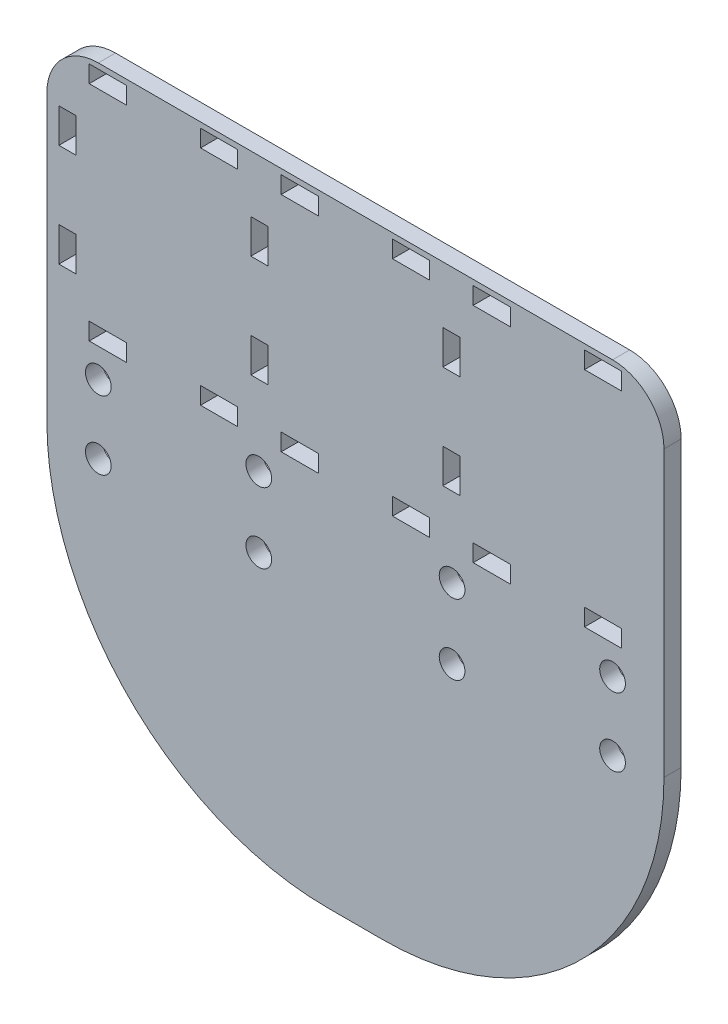
SolidWorks part; units mm, degrees
ref_plane "Front Plane" through (0, 0, 0) normal (0, 0, 1) x (1, 0, 0)
ref_plane "Top Plane" through (0, 0, 0) normal (0, 1, 0) x (1, 0, 0)
ref_plane "Right Plane" through (0, 0, 0) normal (1, 0, 0) x (0, 0, -1)
sketch "Sketch1" plane through (0, 0, 0) normal (0, 0, 1) x (1, 0, 0)
  line L1 (0, 0) -> (228.6, 0)
  line L2 (0, 0) -> (0, 228.6)
  line L3 (0, 228.6) -> (228.6, 228.6)
  line L4 (228.6, 0) -> (228.6, 228.6)
  dimension "D1" = 228.6
  dimension "D2" = 228.6
extrude "Boss-Extrude1" add sketch "Sketch1" along normal blind 6.35
sketch "Sketch2" plane through (0, 0, 6.35) normal (0, 0, 1) x (1, 0, 0)
  line L0 (114.3, 228.6) -> (114.3, 0) construction
  line L1 (228.6, 228.6) -> (0, 228.6) construction
  line L2 (0, 0) -> (228.6, 0) construction
  line L3 (141.8, 226.6) -> (128.05, 226.6)
  line L4 (86.8, 220.25) -> (100.55, 220.25)
  line L5 (86.8, 220.25) -> (86.8, 226.6)
  line L6 (86.8, 226.6) -> (100.55, 226.6)
  line L7 (100.55, 220.25) -> (100.55, 226.6)
  line L8 (86.8, 220.25) -> (100.55, 226.6) construction
  line L9 (86.8, 226.6) -> (100.55, 220.25) construction
  line L10 (128.05, 220.25) -> (128.05, 226.6)
  line L11 (141.8, 220.25) -> (128.05, 220.25)
  line L12 (141.8, 220.25) -> (141.8, 226.6)
  line L13 (185.42, 228.6) -> (185.42, 0) construction
  line L14 (212.92, 226.6) -> (199.17, 226.6)
  line L15 (157.92, 220.25) -> (171.67, 220.25)
  line L16 (157.92, 220.25) -> (157.92, 226.6)
  line L17 (157.92, 226.6) -> (171.67, 226.6)
  line L18 (171.67, 220.25) -> (171.67, 226.6)
  line L19 (157.92, 220.25) -> (171.67, 226.6) construction
  line L20 (157.92, 226.6) -> (171.67, 220.25) construction
  line L21 (199.17, 220.25) -> (199.17, 226.6)
  line L22 (212.92, 220.25) -> (199.17, 220.25)
  line L23 (212.92, 220.25) -> (212.92, 226.6)
  line L24 (15.68, 220.25) -> (15.68, 226.6)
  line L25 (15.68, 220.25) -> (29.43, 220.25)
  line L26 (29.43, 220.25) -> (29.43, 226.6)
  line L27 (15.68, 226.6) -> (29.43, 226.6)
  line L28 (70.68, 226.6) -> (56.93, 226.6)
  line L29 (56.93, 220.25) -> (56.93, 226.6)
  line L30 (70.68, 220.25) -> (56.93, 220.25)
  line L31 (70.68, 220.25) -> (70.68, 226.6)
  line L32 (0, 182.15) -> (228.6, 182.15) construction
  line L33 (0, 228.6) -> (0, 0) construction
  line L34 (228.6, 0) -> (228.6, 228.6) construction
  line L35 (212.92, 144.05) -> (212.92, 137.7)
  line L36 (212.92, 144.05) -> (199.17, 144.05)
  line L37 (199.17, 144.05) -> (199.17, 137.7)
  line L38 (212.92, 137.7) -> (199.17, 137.7)
  line L39 (157.92, 137.7) -> (171.67, 137.7)
  line L40 (171.67, 144.05) -> (171.67, 137.7)
  line L41 (157.92, 144.05) -> (171.67, 144.05)
  line L42 (157.92, 144.05) -> (157.92, 137.7)
  line L43 (141.8, 144.05) -> (141.8, 137.7)
  line L44 (141.8, 144.05) -> (128.05, 144.05)
  line L45 (128.05, 144.05) -> (128.05, 137.7)
  line L46 (141.8, 137.7) -> (128.05, 137.7)
  line L47 (86.8, 137.7) -> (100.55, 137.7)
  line L48 (100.55, 144.05) -> (100.55, 137.7)
  line L49 (86.8, 144.05) -> (100.55, 144.05)
  line L50 (86.8, 144.05) -> (86.8, 137.7)
  line L51 (70.68, 144.05) -> (70.68, 137.7)
  line L52 (70.68, 144.05) -> (56.93, 144.05)
  line L53 (56.93, 144.05) -> (56.93, 137.7)
  line L54 (70.68, 137.7) -> (56.93, 137.7)
  line L55 (15.68, 144.05) -> (29.43, 144.05)
  line L56 (29.43, 144.05) -> (29.43, 137.7)
  line L57 (15.68, 137.7) -> (29.43, 137.7)
  line L58 (15.68, 144.05) -> (15.68, 137.7)
  point P6 (93.675, 223.425)
  point P18 (164.795, 223.425)
  dimension "D1" = 13.75
  dimension "D2" = 13.75
  dimension "D3" = 6.35
  dimension "D4" = 2
  dimension "D5" = 71.12
  dimension "D6" = 13.75
  dimension "D7" = 2
  dimension "D8" = 13.75
  dimension "D9" = 6.35
  dimension "D10" = 38.1
extrude "Cut-Extrude1" cut sketch "Sketch2" against normal through all both and the other way through all
sketch "Sketch3" plane through (0, 0, 6.35) normal (0, 0, 1) x (1, 0, 0)
  line L0 (114.3, 228.6) -> (114.3, 0) construction
  line L1 (228.6, 228.6) -> (0, 228.6) construction
  line L2 (0, 0) -> (228.6, 0) construction
  line L3 (0, 114.3) -> (228.6, 114.3) construction
  line L4 (0, 228.6) -> (0, 0) construction
  line L5 (228.6, 0) -> (228.6, 228.6) construction
  line L6 (0, 127) -> (228.6, 127) construction
  circle A0 centre (19.05, 127) radius 4.7625
  circle A1 centre (19.05, 101.6) radius 4.7625
  circle A2 centre (209.55, 101.6) radius 4.7625
  circle A3 centre (209.55, 127) radius 4.7625
  dimension "D2" = 9.525
  dimension "D1" = 12.7
  dimension "D3" = 95.25
extrude "Cut-Extrude2" cut sketch "Sketch3" against normal through all both and the other way through all
fillet "Fillet1" radius 19.05 2 edges at (228.6, 228.6, 3.175) (0, 228.6, 3.175)
fillet "Fillet2" radius 104.14 2 edges at (228.6, 0, 3.175) (0, 0, 3.175)
sketch "Sketch4" plane through (0, 0, 6.35) normal (0, 0, 1) x (1, 0, 0)
  line L0 (114.3, 228.6) -> (114.3, 0) construction
  line L1 (209.55, 228.6) -> (19.05, 228.6) construction
  line L2 (104.14, 0) -> (124.46, 0) construction
  line L3 (78.74, 223.4204) -> (78.74, 217.4708) construction
  line L4 (86.8, 223.4157) -> (70.68, 223.425) construction
  line L5 (78.74, 223.4204) -> (78.74, 191.1137) construction
  line L6 (29.43, 223.425) -> (56.93, 223.425) construction
  line L7 (63.805, 220.25) -> (63.805, 144.05) construction
  line L8 (75.565, 194.85) -> (81.915, 194.85)
  line L9 (75.565, 194.85) -> (75.565, 207.55)
  line L10 (75.565, 207.55) -> (81.915, 207.55)
  line L11 (81.915, 194.85) -> (81.915, 207.55)
  line L12 (75.565, 194.85) -> (81.915, 207.55) construction
  line L13 (75.565, 207.55) -> (81.915, 194.85) construction
  line L14 (70.68, 220.25) -> (56.93, 220.25) construction
  line L15 (56.93, 144.05) -> (70.68, 144.05) construction
  line L16 (-10.0822, 182.15) -> (230.9345, 182.15) construction
  line L17 (29.43, 220.25) -> (15.68, 220.25) construction
  line L18 (75.565, 156.75) -> (81.915, 156.75)
  line L19 (81.915, 169.45) -> (81.915, 156.75)
  line L20 (75.565, 169.45) -> (81.915, 169.45)
  line L21 (75.565, 169.45) -> (75.565, 156.75)
  line L22 (153.035, 169.45) -> (153.035, 156.75)
  line L23 (153.035, 169.45) -> (146.685, 169.45)
  line L24 (146.685, 169.45) -> (146.685, 156.75)
  line L25 (153.035, 156.75) -> (146.685, 156.75)
  line L26 (153.035, 207.55) -> (146.685, 207.55)
  line L27 (146.685, 194.85) -> (146.685, 207.55)
  line L28 (153.035, 194.85) -> (146.685, 194.85)
  line L29 (153.035, 194.85) -> (153.035, 207.55)
  line L30 (29.43, 226.6) -> (29.43, 220.25) construction
  line L31 (56.93, 220.25) -> (56.93, 226.6) construction
  line L32 (70.68, 221.6996) -> (70.68, 190.0494) construction
  line L33 (70.68, 226.6) -> (70.68, 220.25) construction
  line L34 (86.8, 220.25) -> (86.8, 226.6) construction
  line L35 (43.18, 223.425) -> (43.18, 172.1417) construction
  line L36 (10.795, 169.45) -> (10.795, 156.75)
  line L37 (10.795, 169.45) -> (4.445, 169.45)
  line L38 (4.445, 169.45) -> (4.445, 156.75)
  line L39 (10.795, 156.75) -> (4.445, 156.75)
  line L40 (10.795, 207.55) -> (4.445, 207.55)
  line L41 (4.445, 194.85) -> (4.445, 207.55)
  line L42 (10.795, 194.85) -> (4.445, 194.85)
  line L43 (10.795, 194.85) -> (10.795, 207.55)
  point P12 (78.74, 201.2)
  dimension "D1" = 6.35
  dimension "D2" = 12.7
  dimension "D3" = 12.7
  dimension "D4" = 38.1
  dimension "D5" = 0
extrude "Cut-Extrude3" cut sketch "Sketch4" against normal through all both and the other way through all
sketch "Sketch5" plane through (0, 0, 6.35) normal (0, 0, 1) x (1, 0, 0)
  line L0 (114.3, 228.6) -> (114.3, 0) construction
  line L1 (209.55, 228.6) -> (19.05, 228.6) construction
  line L2 (104.14, 0) -> (124.46, 0) construction
  line L3 (0, 114.3) -> (228.6, 114.3) construction
  line L4 (0, 209.55) -> (0, 104.14) construction
  line L5 (228.6, 104.14) -> (228.6, 209.55) construction
  line L8 (149.86, 156.75) -> (149.86, 114.3) construction
  line L9 (153.035, 156.75) -> (146.685, 156.75) construction
  line L10 (114.3, 114.3) -> (78.4977, 127.331) construction
  circle A0 centre (78.4977, 127.331) radius 4.7625
  circle A1 centre (150.1023, 127.331) radius 4.7625
  circle A2 centre (150.1023, 101.269) radius 4.7625
  circle A3 centre (78.4977, 101.269) radius 4.7625
  dimension "D2" = 9.525
  dimension "D1" = 20
  dimension "D3" = 38.1
extrude "Cut-Extrude4" cut sketch "Sketch5" against normal through all both and the other way through all
equation "\"Wheel Thickness\"= 1in"
equation "\"Wheel Diameter\"= 3in"
equation "\"Motor Rear Diameter\" = 36.2mm"
equation "\"Motor Front Diameter\" = 12mm"
equation "\"Material Thickness\" = .25in"
equation "\"Wheel Cutout Diameter\"= 2cm"
equation "\"Motor Mount Tab Thickness\" = 100mm"
equation "\"Motor Mount Tab Height\" = 40mm"
equation "\"Motor Shaft Diameter\" = 3mm"
equation "\"Wheel Radius Clearance\" = 5mm"
equation "\"Wheel Cutout Width\" = 1.5in"
equation "\"Base Diameter\" = 10in"
equation "\"Wheel Mount Distance\" = 5mm"
equation "\"Motor Mount Distance\" = 50mm"
equation "\"Motor Cutout Length\" = 6in"
equation "\"Motor Cutout Height\" = 2in "
equation "\"Rod Diameter\" = 3/8in"
equation "\"Rod Length\" = 1.5in"
equation "\"Barrel Front Length\" = 1.8in"
equation "\"Barrerl Rear Length\" = 5in "
equation "\"Barrel Fillet Radius\" = 1in "
equation "\"Barrel Angle\" = 20deg"
equation "\"Barrel Diameter\" = 50mm"
equation "\"Barrel Shell Width\" = 2mm"
equation "\"Second Level Diameter\" = 10in"
equation "\"Ball Diameter\" = 40mm"
equation "\"Third Level Length\" = 9in"
equation "\"Third Level Height\" = 9in"
equation "\"D1@Sketch1\"=\"Third Level Height\""
equation "\"D2@Sketch1\"=\"Third Level Length\""
equation "\"D1@Boss-Extrude1\"=\"Material Thickness\""
equation "\"Barrel Tab Clearance\" = 5mm"
equation "\"D1@Sketch2\"=((\"Barrel Diameter\")+\"Barrel Tab Clearance\")/4"
equation "\"D2@Sketch2\"=((\"Barrel Diameter\")+\"Barrel Tab Clearance\")/4"
equation "\"D3@Sketch2\"=\"Material Thickness\""
equation "\"Barrel Tab Distance Away\" = 2mm"
equation "\"D4@Sketch2\"=\"Barrel Tab Distance Away\""
equation "\"Hole Distance Apart\" = 2.8in"
equation "\"D5@Sketch2\" = \"Hole Distance Apart\""
equation "\"D6@Sketch2\"=((\"Barrel Diameter\")+\"Barrel Tab Clearance\")/4"
equation "\"D7@Sketch2\"=\"Barrel Tab Distance Away\""
equation "\"D8@Sketch2\"=((\"Barrel Diameter\")+\"Barrel Tab Clearance\")/4"
equation "\"D9@Sketch2\"=\"Material Thickness\""
equation "\"Barrel Tab Distance\"= 1.5in "
equation "\"D10@Sketch2\"=\"Barrel Tab Distance\""
equation "\"Third Level Rod Distance\" = .5in"
equation "\"D1@Sketch3\"=\"Third Level Rod Distance\""
equation "\"D2@Sketch3\"=\"Rod Diameter\""
equation "\"D3@Sketch3\"=(\"Base Diameter\"/2)*.75"
equation "\"D1@Sketch4\"=\"Material Thickness\""
equation "\"Servo Hole Diameter\" = 1/4in"
equation " \"Second Rod Diameter\" = 3/8in"
equation "\"Second Rod Length\" = 3.88in"
equation "\"Bumper Rod Length\"= 2in"
equation "\"Bumper Wheel Clearance\" = 1.2in"
equation "\"Servo Tab Height\" = 4in"
equation "\"Servo Tab Width\" = 2in"
equation "\"Servo Tab Hole Horizontal Distance\" = 1in"
equation "\"Servo Tab Hole Vertical Distance\" = 1.5in "
equation "\"Servo Hole Vertical Distance\" = 3in"
equation "\"D2@Sketch4\"=\"Servo Tab Width\"/4"
equation "\"D3@Sketch4\"=\"Servo Tab Width\"/4"
equation "\"D4@Sketch4\"=\"Barrel Tab Distance\""
equation "\"Servo Hole Shaft Length\" = 1.45in"
equation "\"Third Rod Length\" = 3.83in"
equation "\"Third Rod Diameter\" = 3/8in"
equation "\"Third Rod Radius Distance\" = 1.5in"
equation "\"Third Rod Angle Distance\" = 20deg"
equation "\"D1@Sketch5\"=\"Third Rod Angle Distance\""
equation "\"D2@Sketch5\"=\"Third Rod Diameter\""
equation "\"D3@Sketch5\"=\"Third Rod Radius Distance\""
